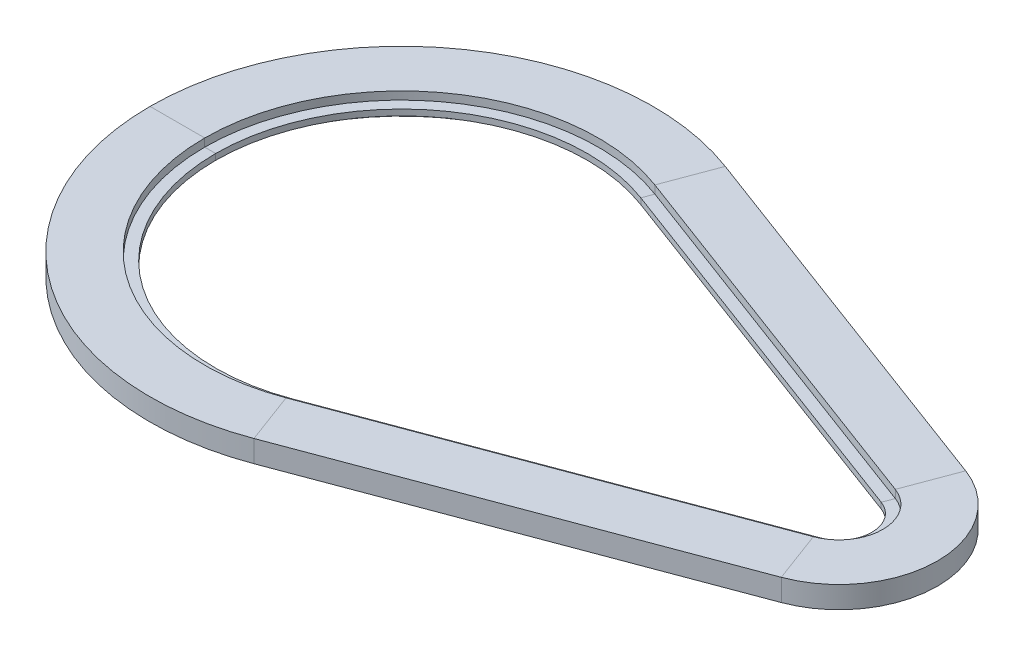
SolidWorks part; units mm, degrees
ref_plane "Front Plane" through (0, 0, 0) normal (0, 0, 1) x (1, 0, 0)
ref_plane "Top Plane" through (0, 0, 0) normal (0, 1, 0) x (1, 0, 0)
ref_plane "Right Plane" through (0, 0, 0) normal (1, 0, 0) x (0, 0, -1)
sketch "Sketch2" plane through (0, 0, 0) normal (0, 1, 0) x (1, 0, 0)
  line L0 (0, 0) -> (127, 0) construction
  line L1 (131.445, 11.8967) -> (20.0025, 53.5352)
  line L2 (20.0025, -53.5352) -> (131.445, -11.8967)
  arc A0 (20.0025, 53.5352) -> (20.0025, -53.5352) centre (0, 0) ccw
  arc A1 (131.445, -11.8967) -> (131.445, 11.8967) centre (127, 0) ccw
  dimension "D1" = 114.3
  dimension "D3" = 25.4
  dimension "D2" = 127
sketch "Sketch3" plane through (0, 0, 0) normal (0, 0, 1) x (1, 0, 0)
  line L0 (0, 0) -> (-57.15, 0) construction
  line L1 (20.0025, 0) -> (-57.15, 0) construction
  line L2 (-57.15, 3.175) -> (-73.025, 3.175)
  line L3 (-73.025, 3.175) -> (-73.025, -3.175)
  line L4 (-73.025, -3.175) -> (-57.15, -3.175)
  line L5 (-57.15, -3.175) -> (-57.15, -0.8636)
  line L6 (-57.15, -0.8636) -> (-53.975, -0.8636)
  line L7 (-53.975, -0.8636) -> (-53.975, 0.8636)
  line L8 (-53.975, 0.8636) -> (-57.15, 0.8636)
  line L9 (-57.15, 0.8636) -> (-57.15, 3.175)
  point P7 (-53.975, 0)
  point P14 (-73.025, 0)
  point P15 (0, 0)
  dimension "D1" = 57.15
  dimension "D2" = 1.7272
  dimension "D3" = 6.35
  dimension "D4" = 15.875
  dimension "D5" = 3.175
sweep "Sweep1" add profiles "Sketch3" path "Sketch2"
